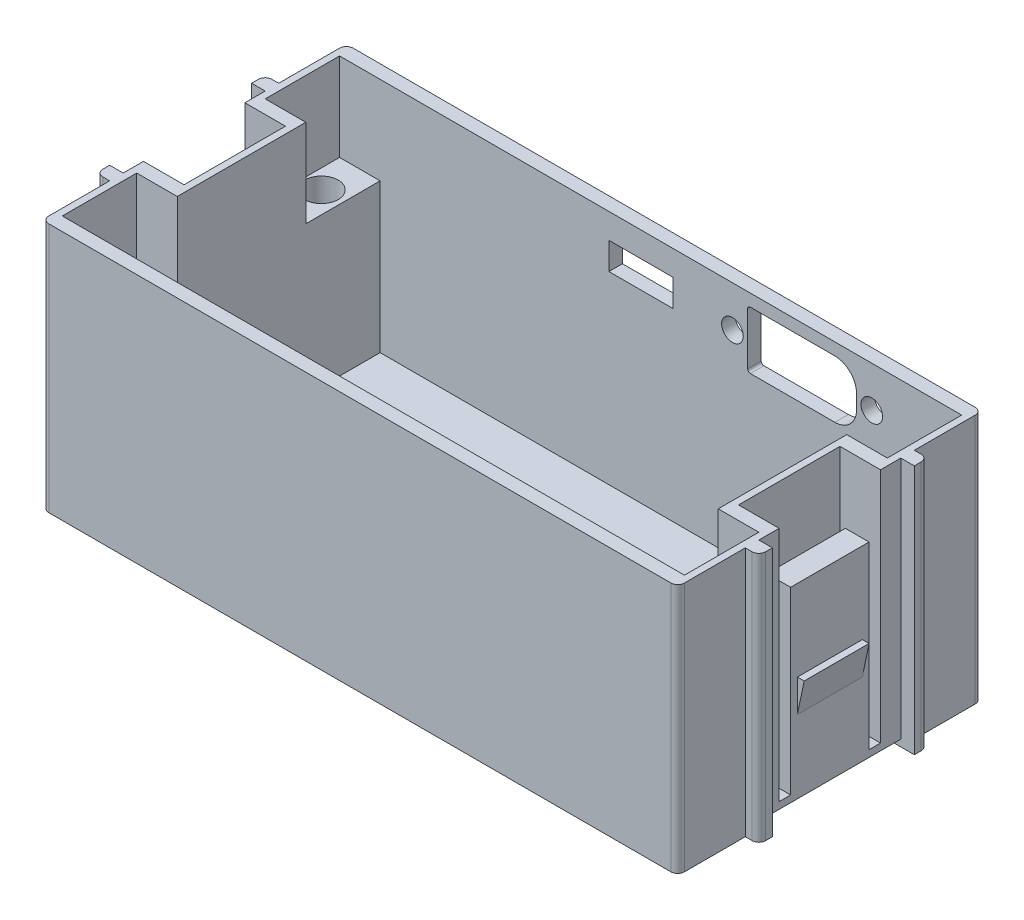
SolidWorks part; units mm, degrees
ref_plane "Front Plane" through (0, 0, 0) normal (0, 0, 1) x (1, 0, 0)
ref_plane "Top Plane" through (0, 0, 0) normal (0, 1, 0) x (1, 0, 0)
ref_plane "Right Plane" through (0, 0, 0) normal (1, 0, 0) x (0, 0, -1)
sketch "Sketch1" plane through (0, 0, 0) normal (0, 1, 0) x (1, 0, 0)
  line L1 (0, 0) -> (-47, 0)
  line L2 (0, 0) -> (0, 45)
  line L3 (0, 45) -> (-47, 45)
  line L4 (-47, 0) -> (-47, 45)
  dimension "D1" = 45
  dimension "D2" = 47
extrude "Boss-Extrude1" add sketch "Sketch1" along normal blind 2
sketch "Sketch4" plane through (0, 2, 0) normal (0, 1, 0) x (1, 0, 0)
  line L0 (-86.5, 22.5) -> (-39.75, 22.5) construction
  line L1 (-47, 15) -> (-47, 0)
  line L2 (-42, 15) -> (-47, 15)
  line L3 (-42, 15) -> (-42, 30)
  line L4 (0, 0) -> (0, 45)
  line L5 (0, 45) -> (-47, 45)
  line L6 (-47, 45) -> (-47, 0)
  line L7 (-47, 0) -> (0, 0)
  line L9 (0, 45) -> (-47, 45)
  line L10 (-47, 45) -> (-47, 30)
  line L11 (-47, 0) -> (0, 0)
  line L12 (-42, 30) -> (-47, 30)
  line L14 (-42, 15) -> (-47, 30) construction
  line L15 (-42, 30) -> (-47, 15) construction
  line L20 (-2, 43) -> (0, 43)
  line L21 (0, 30) -> (0, 45) construction
  line L22 (0, 43) -> (0, 45)
  line L28 (-2, 43) -> (-45, 43)
  line L30 (-40, 32) -> (-45, 32)
  line L32 (-40, 13) -> (-45, 13)
  line L34 (-45, 2) -> (-2, 2)
  line L37 (-0.8642, 2) -> (-2, 2)
  line L39 (-2, 2) -> (-2, 13) construction
  line L42 (-0.8642, 2) -> (0, 2)
  line L43 (-2, 32) -> (-2, 43) construction
  line L44 (0, 0) -> (0, 45) construction
  line L45 (0, 2) -> (0, 0)
  line L46 (-40, 13) -> (-40, 32) construction
  line L47 (-5, 15) -> (-5, 30) construction
  line L48 (-7, 13) -> (-2, 13) construction
  line L49 (-7, 13) -> (-7, 32) construction
  line L50 (-7, 32) -> (-2, 32) construction
  line L51 (-5, 15) -> (0, 15) construction
  line L52 (-5, 30) -> (0, 30) construction
  line L53 (0, 0) -> (0, 15) construction
  line L54 (-45, 2) -> (-46, 2)
  line L56 (-45, 13) -> (-46, 13)
  line L57 (-46, 2) -> (-46, 13)
  line L58 (-45, 13) -> (-45, 2) construction
  line L59 (-45, 32) -> (-46, 32)
  line L61 (-45, 43) -> (-46, 43)
  line L62 (-46, 32) -> (-46, 43)
  line L63 (-45, 43) -> (-45, 32) construction
  line L64 (-40, 32) -> (-40, 13) construction
  line L67 (-40, 32) -> (-40, 13)
  point P7 (-44.5, 22.5)
  line M25 (0, 0) -> (0, 45)
  line M26 (0, 45) -> (-47, 45)
  line M27 (-47, 45) -> (-47, 0)
  line M28 (-47, 0) -> (0, 0)
  dimension "D2" = 15
  dimension "D3" = 1
  dimension "D4" = 5
  dimension "D5" = 1
  dimension "D6" = 2
  dimension "D1" = 0
extrude "Boss-Extrude3" add sketch "Sketch4" along normal blind 35 contours L67 L30 L59 L62 L61 L28 L20 L12 L3 L2 L42 L37 L34 L54 L57 L56 L32 M25 M26 M27 M28
ref_plane "Plane1" through (0, 0, -22.5) normal (0, 0, 1) x (1, 0, 0)
sketch "Sketch5" plane through (0, 0, -22.5) normal (0, 0, 1) x (1, 0, 0)
  line L0 (-47, 2) -> (-42, 2) construction
  line L1 (-47, 2) -> (-42, 2) construction
  line L2 (-47, 2) -> (-47, 11.8)
  line L5 (-47, 16.6) -> (-47, 28.6)
  line L6 (-47, 28.6) -> (-43.5, 28.6)
  line L7 (-43.5, 28.6) -> (-43.5, 2)
  line L8 (-43.5, 2) -> (-47, 2)
  line L9 (-47, 16.6) -> (-48, 16.6)
  line L10 (-48, 16.6) -> (-47, 11.8)
  dimension "D1" = 3.5
  dimension "D2" = 1
  dimension "D3" = 3.5
  dimension "D4" = 9.8
  dimension "D5" = 4.8
  dimension "D6" = 12
extrude "Boss-Extrude4" add sketch "Sketch5" along normal blind 4.8 and the other way blind 4.8
sketch "Sketch6" plane through (0, 0, 0) normal (0, -1, 0) x (-1, 0, 0)
  line L0 (47, 45) -> (47, 0) construction
  line L1 (47, 45) -> (47, 0)
  line L3 (47, 33) -> (49, 33)
  line L4 (49, 33) -> (49, 12) construction
  line L5 (49, 12) -> (47, 12)
  line L6 (-20.35, 22.5) -> (20.35, 22.5) construction
  line L7 (49, 33) -> (49, 35)
  line L8 (49, 35) -> (47, 35)
  line L9 (49, 12) -> (49, 10)
  line L10 (49, 10) -> (47, 10)
  line L11 (47, 12) -> (47, 10)
  line L12 (47, 33) -> (47, 35)
  dimension "D1" = 10.5
  dimension "D2" = 10.5
  dimension "D3" = 2
  dimension "D4" = 2
  dimension "D5" = 2
extrude "Boss-Extrude5" add sketch "Sketch6" against normal up to vertex (37 mm away) contours L7 L8 L1 L3 | L10 L9 L5 L1
sketch "Sketch13" plane through (0, 2, 0) normal (0, 1, 0) x (1, 0, 0)
  line L0 (0, 2) -> (-46, 2) construction
  line L1 (-46, 43) -> (-40, 43)
  line L2 (-46, 43) -> (-46, 32)
  line L3 (-46, 32) -> (-40, 32)
  line L4 (-40, 43) -> (-40, 32)
  line L5 (-46, 13) -> (-40, 13)
  line L6 (-46, 13) -> (-46, 2)
  line L7 (-46, 2) -> (-40, 2)
  line L8 (-40, 13) -> (-40, 2)
extrude "Boss-Extrude7" add sketch "Sketch13" along normal blind 22
sketch "Sketch23" plane through (0, 0, -17.7) normal (0, 0, 1) x (1, 0, 0)
  line L1 (-43.5, 28.6) -> (-47, 28.6)
  line L2 (-43.5, 28.6) -> (-43.5, 2)
  line L3 (-43.5, 2) -> (-47, 2)
  line L4 (-47, 28.6) -> (-47, 2)
extrude "Boss-Extrude9" add sketch "Sketch23" along normal blind 1
sketch "Sketch24" plane through (0, 0, -27.3) normal (0, 0, -1) x (-1, 0, 0)
  line L1 (47, 2) -> (43.5, 2)
  line L2 (47, 2) -> (47, 28.6)
  line L3 (47, 28.6) -> (43.5, 28.6)
  line L4 (43.5, 2) -> (43.5, 28.6)
extrude "Boss-Extrude10" add sketch "Sketch24" along normal blind 1
hole_wizard "Hole2" positions "3DSketch2" profile "Sketch15" legacy
sketch3d "3DSketch2"
  line L0 (-43.2, 24, -13) -> (-43.2, 24, -2) construction
  line L1 (-40, 24, -13) -> (-46, 24, -13) construction
  line L2 (-46, 24, -2) -> (-40, 24, -2) construction
  line L4 (-46, 24, -13) -> (-46, 24, -2) construction
  line L5 (-43.2, 24, -43) -> (-43.2, 24, -32) construction
  line L6 (-40, 24, -43) -> (-46, 24, -43) construction
  line L7 (-46, 24, -32) -> (-40, 24, -32) construction
  line L9 (-46, 24, -43) -> (-46, 24, -32) construction
  point P0 (-43.2, 24, -7.5)
  point P2 (-43.2, 24, -37.5)
  dimension "D1" = 2.8
  dimension "D2" = 2.8
sketch "Sketch15" plane through (-43.2, 24, -7.5) normal (1, 0, 0) x (0, 0, 1)
  line L0 (0, 0) -> (0, 15)
  line L1 (0, 15) -> (1.6, 15)
  line L2 (1.6, 15) -> (1.6, 5)
  line L3 (1.6, 5) -> (2.5, 5)
  line L4 (2.5, 5) -> (2.5, 0)
  line L5 (2.5, 0) -> (0, 0)
  line L6 (0, 110) -> (0, -10) construction
  dimension "Diameter" = 3.2
  dimension "Depth" = 15
  dimension "C-Bore Diameter" = 5
  dimension "C-Bore Depth" = 5
ref_plane "Plane2" through (0, 0, 0) normal (1, 0, 0) x (0, 0, -1)
fillet "Fillet1" radius 1 4 edges at (-47, 18.5, 0) (-47, 18.5, -45) (-49, 18.5, -35) (-49, 18.5, -10)
fillet "Fillet2" radius 1 1 edges at (-43.5, 2, -22.5)
sketch "Sketch25" plane through (0, 37, 0) normal (0, 1, 0) x (1, 0, 0)
  line L0 (-42, 15) -> (-47, 15) construction
  line L1 (-42, 30) -> (-41, 30)
  line L2 (-42, 30) -> (-42, 15)
  line L3 (-42, 15) -> (-41, 15)
  line L4 (-41, 30) -> (-41, 15)
  dimension "D1" = 1
extrude "Cut-Extrude5" cut sketch "Sketch25" against normal up to surface (35 mm away) up to face at (-44.625, 2, -22.5)
mirror "Mirror1" about plane through (0, 0, 0) normal (1, 0, 0) of "Cut-Extrude5", "Fillet2", "Hole2", "Boss-Extrude7", "Boss-Extrude4", "Boss-Extrude3", "Boss-Extrude1", "Boss-Extrude5", "Fillet1", "Boss-Extrude9", "Boss-Extrude10"
chamfer "Chamfer1" distance 1 angle 45 2 edges at (47, 0, -22.5) (-47, 0, -22.5)
sketch "Sketch17" plane through (0, 24, 0) normal (0, 1, 0) x (1, 0, 0)
  line L0 (46, 2) -> (-46, 2)
  line L1 (-46, 2) -> (-46, 13)
  line L2 (-46, 13) -> (-40, 13)
  line L3 (-40, 13) -> (-40, 32)
  line L4 (-40, 32) -> (-46, 32)
  line L5 (-46, 32) -> (-46, 43)
  line L6 (-46, 43) -> (46, 43)
  line L7 (46, 43) -> (46, 32)
  line L8 (46, 32) -> (40, 32)
  line L9 (40, 32) -> (40, 13)
  line L10 (40, 13) -> (46, 13)
  line L11 (46, 13) -> (46, 2)
  line L12 (-46, 43) -> (-46, 32) construction
  line L13 (-46, 32) -> (-40, 32) construction
  circle A0 centre (43.2, 7.5) radius 2.5 construction
  circle A1 centre (43.2, 7.5) radius 2.5
  circle A2 centre (-43.2, 37.5) radius 2.5 construction
  circle A3 centre (-43.2, 7.5) radius 2.5 construction
  circle A4 centre (43.2, 37.5) radius 2.5 construction
  circle A5 centre (-43.2, 37.5) radius 2.5
  circle A6 centre (-43.2, 7.5) radius 2.5
  circle A7 centre (43.2, 37.5) radius 2.5
  dimension "D4" = 5.5
  dimension "D5" = 2.8
  dimension "D6" = 89.2
  dimension "D1" = 92
  dimension "D2" = 41
  dimension "D3" = 11
extrude "Cut-Extrude1" cut sketch "Sketch19" against normal blind 10
sketch "Sketch19" plane through (-58.9164, -6.9327, -45) normal (0, 0, -1) x (-1, 0, 0)
  line L0 (-73.6664, 42.1327) -> (-86.1664, 42.1327)
  line L1 (-89.3664, 38.9327) -> (-89.3664, 36.8327)
  line L2 (-86.1664, 33.6327) -> (-73.6664, 33.6327)
  line L3 (-73.2664, 34.0327) -> (-73.2664, 41.7327)
  line L8 (-73.6664, 41.9327) -> (-86.1664, 41.9327) construction
  line L9 (-89.1664, 38.9327) -> (-89.1664, 36.8327) construction
  line L10 (-86.1664, 33.8327) -> (-73.6664, 33.8327) construction
  line L11 (-73.4664, 34.0327) -> (-73.4664, 41.7327) construction
  arc A0 (-86.1664, 42.1327) -> (-89.3664, 38.9327) centre (-86.1664, 38.9327) ccw
  arc A1 (-89.3664, 36.8327) -> (-86.1664, 33.6327) centre (-86.1664, 36.8327) ccw
  arc A2 (-73.6664, 33.6327) -> (-73.2664, 34.0327) centre (-73.6664, 34.0327) ccw
  arc A3 (-73.2664, 41.7327) -> (-73.6664, 42.1327) centre (-73.6664, 41.7327) ccw
  arc A8 (-86.1664, 41.9327) -> (-89.1664, 38.9327) centre (-86.1664, 38.9327) ccw construction
  arc A9 (-89.1664, 36.8327) -> (-86.1664, 33.8327) centre (-86.1664, 36.8327) ccw construction
  arc A10 (-73.6664, 33.8327) -> (-73.4664, 34.0327) centre (-73.6664, 34.0327) ccw construction
  arc A11 (-73.4664, 41.7327) -> (-73.6664, 41.9327) centre (-73.6664, 41.7327) ccw construction
  circle A14 centre (-71.0164, 37.8827) radius 1.325 construction
  circle A15 centre (-91.6164, 37.8827) radius 1.325 construction
  circle A16 centre (-91.6164, 37.8827) radius 1.6
  circle A17 centre (-71.0164, 37.8827) radius 1.6
extrude "Cut-Extrude2" cut sketch "Sketch20" against normal blind 10
sketch "Sketch20" plane through (-58.9164, -6.9327, -45) normal (0, 0, -1) x (-1, 0, 0)
  line L2 (-62.2464, 36.2327) -> (-52.7464, 36.2327)
  line L3 (-62.2464, 36.2327) -> (-62.2464, 40.2327)
  line L12 (-62.2464, 40.2327) -> (-52.7464, 40.2327)
  line L13 (-52.7464, 36.2327) -> (-52.7464, 40.2327)
  line L14 (-62.2464, 36.2327) -> (-52.7464, 40.2327) construction
  line L15 (-62.2464, 40.2327) -> (-52.7464, 36.2327) construction
  point P9 (-57.4964, 38.2327)
sketch "Sketch22" plane through (0, 0, 0) normal (0, 1, 0) x (1, 0, 0)
  line L1 (-40, 17.5) -> (40, 17.5)
  line L2 (-40, 17.5) -> (-40, 27.5)
  line L3 (-40, 27.5) -> (40, 27.5)
  line L4 (40, 17.5) -> (40, 27.5)
  line L5 (40, 32) -> (40, 13) construction
  line L6 (-20.35, 22.5) -> (20.35, 22.5) construction
  line L8 (-40, 35) -> (-40, 10) construction
  dimension "D1" = 5
  dimension "D2" = 5
